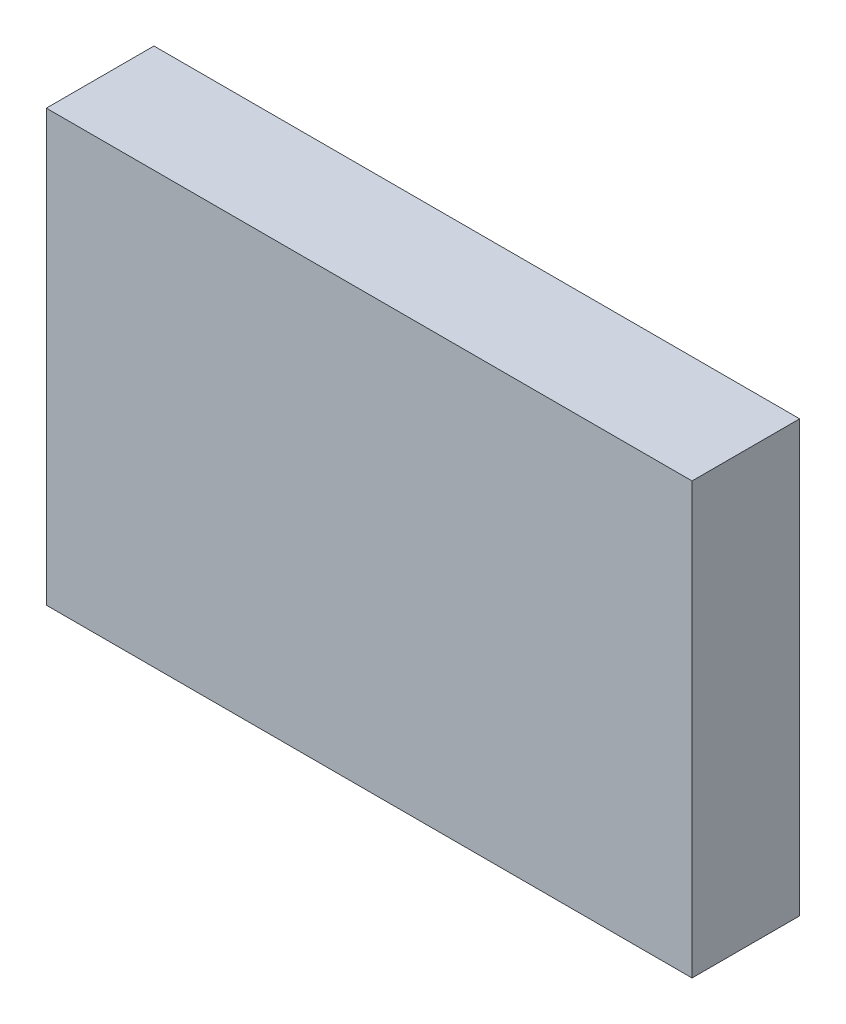
SolidWorks part; units mm, degrees
ref_plane "Front Plane" through (0, 0, 0) normal (0, 0, 1) x (1, 0, 0)
ref_plane "Top Plane" through (0, 0, 0) normal (0, 1, 0) x (1, 0, 0)
ref_plane "Right Plane" through (0, 0, 0) normal (1, 0, 0) x (0, 0, -1)
sketch "Sketch1" plane through (0, 0, 0) normal (1, 0, 0) x (0, 0, -1)
  line L1 (-1.4028, -9.2292) -> (1.5972, -9.2292)
  line L2 (-1.4028, -9.2292) -> (-1.4028, 2.7708)
  line L3 (-1.4028, 2.7708) -> (1.5972, 2.7708)
  line L4 (1.5972, -9.2292) -> (1.5972, 2.7708)
  line L5 (-1.4028, -9.2292) -> (1.5972, 2.7708) construction
  line L6 (-1.4028, 2.7708) -> (1.5972, -9.2292) construction
  dimension "D1" = 3
  dimension "D2" = 12
extrude "Boss-Extrude1" add sketch "Sketch1" along normal blind 18
